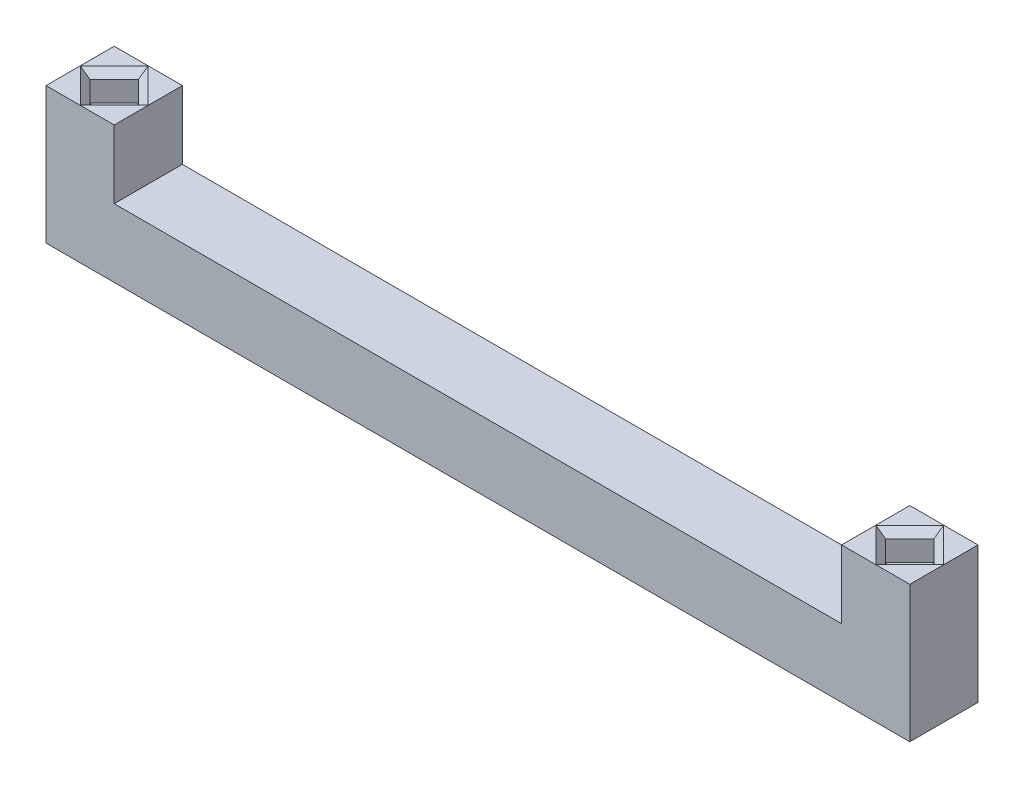
SolidWorks part; units mm, degrees
ref_plane "Front Plane" through (0, 0, 0) normal (0, 0, 1) x (1, 0, 0)
ref_plane "Top Plane" through (0, 0, 0) normal (0, 1, 0) x (1, 0, 0)
ref_plane "Right Plane" through (0, 0, 0) normal (1, 0, 0) x (0, 0, -1)
sketch "Sketch1" plane through (0, 0, 0) normal (0, 0, 1) x (1, 0, 0)
  line L0 (-80.4333, 19.05) -> (-80.4333, -6.35)
  line L1 (-80.4333, -6.35) -> (80.4333, -6.35)
  line L2 (80.4333, -6.35) -> (80.4333, 19.05)
  line L3 (80.4333, 19.05) -> (67.7333, 19.05)
  line L4 (67.7333, 19.05) -> (67.7333, 6.35)
  line L5 (67.7333, 6.35) -> (-67.7333, 6.35)
  line L6 (-67.7333, 6.35) -> (-67.7333, 19.05)
  line L7 (-67.7333, 19.05) -> (-80.4333, 19.05)
  line L8 (-67.7333, 6.35) -> (-67.7333, -6.35) construction
  point P11 (-67.7333, 0)
  point P14 (0, -6.35)
  dimension "D1" = 12.7
  dimension "D2" = 25.4
  dimension "D3" = 160.8667
extrude "Boss-Extrude1" add sketch "Sketch1" along normal blind 12.7
sketch "Sketch2" plane through (0, 19.05, 0) normal (0, 1, 0) x (1, 0, 0)
  line L0 (-78.5735, -6.35) -> (-74.0833, -1.8599)
  line L1 (-78.5735, -6.35) -> (-74.0833, -10.8401)
  line L2 (-74.0833, -1.8599) -> (-69.5932, -6.35)
  line L3 (-74.0833, -10.8401) -> (-69.5932, -6.35)
  line L4 (-78.5735, -6.35) -> (-69.5932, -6.35) construction
  line L5 (-74.0833, -1.8599) -> (-74.0833, -10.8401) construction
  line L6 (-67.7333, 0) -> (-80.4333, 0) construction
  line L7 (-80.4333, -12.7) -> (-80.4333, 0) construction
  line L8 (69.5932, -6.35) -> (74.0833, -1.8599)
  line L9 (69.5932, -6.35) -> (74.0833, -10.8401)
  line L10 (74.0833, -1.8599) -> (78.5735, -6.35)
  line L11 (74.0833, -10.8401) -> (78.5735, -6.35)
  line L12 (69.5932, -6.35) -> (78.5735, -6.35) construction
  line L13 (74.0833, -1.8599) -> (74.0833, -10.8401) construction
  line L14 (80.4333, 0) -> (67.7333, 0) construction
  point P1 (-74.0833, -6.35)
  point P3 (-74.0833, 0)
  point P10 (-80.4333, -6.35)
  point P12 (74.0833, -6.35)
  point P14 (74.0833, 0)
  dimension "D1" = 6.35
  dimension "D2" = 6.35
extrude "Cut-Extrude1" cut sketch "Sketch2" against normal blind 6.35
chamfer "Chamfer1" distance 1.27 angle 45 16 edges at (71.8383, 12.7, 4.1049) (76.3284, 12.7, 4.1049) (76.3284, 12.7, 8.5951) (71.8383, 12.7, 8.5951) (-76.3284, 12.7, 4.1049) (-71.8383, 12.7, 4.1049) (-71.8383, 12.7, 8.5951) (-76.3284, 12.7, 8.5951) (-71.8383, 19.05, 8.5951) (-71.8383, 19.05, 4.1049) (-76.3284, 19.05, 8.5951) (-76.3284, 19.05, 4.1049) (76.3284, 19.05, 4.1049) (76.3284, 19.05, 8.5951) (71.8383, 19.05, 8.5951) (71.8383, 19.05, 4.1049)
